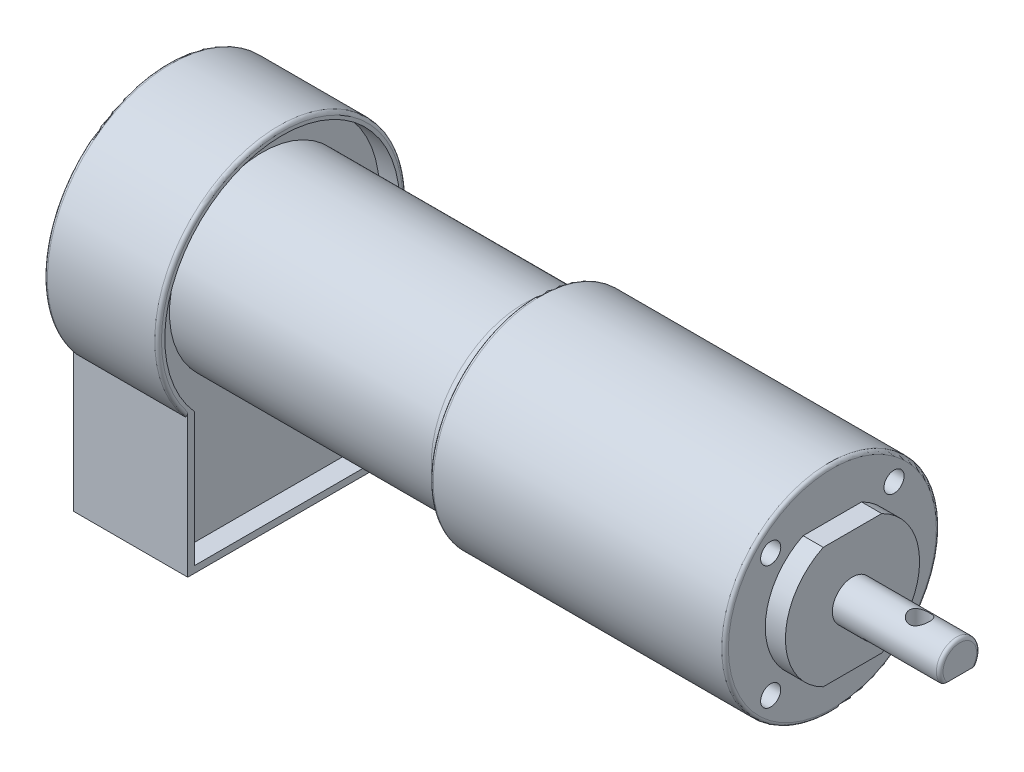
SolidWorks part; units mm, degrees
ref_plane "Front Plane" through (0, 0, 0) normal (0, 0, 1) x (1, 0, 0)
ref_plane "Top Plane" through (0, 0, 0) normal (0, 1, 0) x (1, 0, 0)
ref_plane "Right Plane" through (0, 0, 0) normal (1, 0, 0) x (0, 0, -1)
sketch "Sketch1" plane through (0, 0, 0) normal (1, 0, 0) x (0, 0, -1)
  line L0 (-14.0801, -12) -> (-14.0801, -32.5)
  line L2 (-14.0801, -32.5) -> (14.0801, -32.5)
  line L3 (14.0801, -32.5) -> (14.0801, -12)
  arc A0 (14.0801, -12) -> (-14.0801, -12) centre (0, 0) ccw
  point P3 (0, -32.5)
  dimension "D1" = 37
  dimension "D2" = 28.1603
  dimension "D3" = 20.5
extrude "Boss-Extrude1" add sketch "Sketch1" along normal blind 17
sketch "Sketch10" plane through (17, 0, 0) normal (1, 0, 0) x (0, 0, -1)
  line L0 (-14.0801, -32.5) -> (14.0801, -32.5) construction
  line L1 (13.0801, -31.5) -> (-13.0801, -31.5)
  line L2 (13.0801, -31.5) -> (13.0801, -11.6258)
  line L4 (-13.0801, -31.5) -> (-13.0801, -11.6258)
  line L5 (-14.0801, -12) -> (-14.0801, -32.5) construction
  line L6 (14.0801, -32.5) -> (14.0801, -12) construction
  arc A0 (13.0801, -11.6258) -> (-13.0801, -11.6258) centre (0, 0) ccw
  dimension "D4" = 17.5
  dimension "D1" = 1
  dimension "D2" = 1
  dimension "D3" = 1
extrude "Cut-Extrude5" cut sketch "Sketch10" against normal blind 3
sketch "Sketch2" plane through (14, 0, 0) normal (1, 0, 0) x (0, 0, -1)
  circle A0 centre (0, 0) radius 13.8
extrude "Boss-Extrude2" add sketch "Sketch2" along normal blind 41
fillet "Fillet1" radius 2 1 edges at (55, 0, -13.8)
sketch "Sketch3" plane through (55, 0, 0) normal (1, 0, 0) x (0, 0, -1)
  circle A0 centre (0, 0) radius 16
  dimension "D1" = 32
extrude "Boss-Extrude3" add sketch "Sketch3" along normal blind 44
sketch "Sketch4" plane through (99, 0, 0) normal (1, 0, 0) x (0, 0, -1)
  line L0 (0, 0) -> (0, 9) construction
  line L5 (0, 0) -> (5.9158, 0) construction
  circle A1 centre (9.1924, 9.1924) radius 1.5
  circle A2 centre (9.1924, -9.1924) radius 1.5
  circle A3 centre (-9.1924, -9.1924) radius 1.5
  circle A4 centre (-9.1924, 9.1924) radius 1.5
  point P4 (0, 0)
  point P19 (0, -9)
  dimension "D1" = 9.1924
  dimension "D2" = 3
  dimension "D3" = 9.1924
  dimension "D7" = 13
  dimension "D8" = 13
  dimension "D4" = 4
extrude "Cut-Extrude1" cut sketch "Sketch4" against normal blind 15 contours A3 | A1 | A4 | A2
sketch "Sketch5" plane through (99, 0, 0) normal (1, 0, 0) x (0, 0, -1)
  line L1 (-4.3589, -9) -> (4.3589, -9)
  line L2 (-4.3589, 9) -> (4.3589, 9)
  arc A0 (4.3589, 9) -> (4.3589, -9) centre (0, 0) cw
  arc A1 (-4.3589, -9) -> (-4.3589, 9) centre (0, 0) cw
  point P2 (0, 9)
  point P4 (0, -9)
  dimension "D2" = 10
  dimension "D1" = 18
extrude "Boss-Extrude5" add sketch "Sketch5" along normal blind 3
sketch "Sketch6" plane through (102, 0, 0) normal (1, 0, 0) x (0, 0, -1)
  circle A0 centre (0, 0) radius 3
extrude "Boss-Extrude6" add sketch "Sketch6" along normal blind 16
sketch "Sketch7" plane through (118, 0, 0) normal (1, 0, 0) x (0, 0, -1)
  line L0 (-2.5055, -1.65) -> (2.5055, -1.65)
  arc A2 (-2.5055, -1.65) -> (2.5055, -1.65) centre (0, 0) ccw
  dimension "D1" = 3
  dimension "D2" = 1.65
extrude "Cut-Extrude2" cut sketch "Sketch7" against normal blind 12
fillet "Fillet2" radius 0.5 5 edges at (17, 18.5, 0) (0, 18.5, 0) (118, 3, 0) (55, 0, -16) (99, 0, -16)
sketch "Sketch8" plane through (0, -1.65, 0) normal (0, -1, 0) x (1, 0, 0)
  line L0 (106, -2.5055) -> (106, 2.5055) construction
  line L3 (117.5, 3) -> (102, 3) construction
  circle A0 centre (112, 0) radius 1.5
  dimension "D1" = 3
  dimension "D2" = 6
  dimension "D3" = 3
extrude "Cut-Extrude3" cut sketch "Sketch8" against normal up to next
sketch "Sketch9" plane through (0, 0, 0) normal (-1, 0, 0) x (0, 0, 1)
  line L0 (14.0801, -32.5) -> (-14.0801, -32.5) construction
  line L1 (13.0801, -31.5) -> (-13.0801, -31.5)
  line L2 (13.0801, -31.5) -> (13.0801, -11.2138)
  line L3 (13.0801, -11.2138) -> (11.4617, -11.2138)
  line L4 (-13.0801, -31.5) -> (-13.0801, -11.2138)
  line L5 (14.0801, -11.2138) -> (14.0801, -32.5) construction
  line L6 (-14.0801, -32.5) -> (-14.0801, -11.2138) construction
  line L7 (-11.4617, -11.2138) -> (-13.0801, -11.2138)
  arc A1 (11.4617, -11.2138) -> (-11.4617, -11.2138) centre (0, 0) cw
  dimension "D1" = 1
  dimension "D2" = 1
  dimension "D3" = 1
  dimension "D4" = 0
extrude "Cut-Extrude4" cut sketch "Sketch9" against normal blind 10
